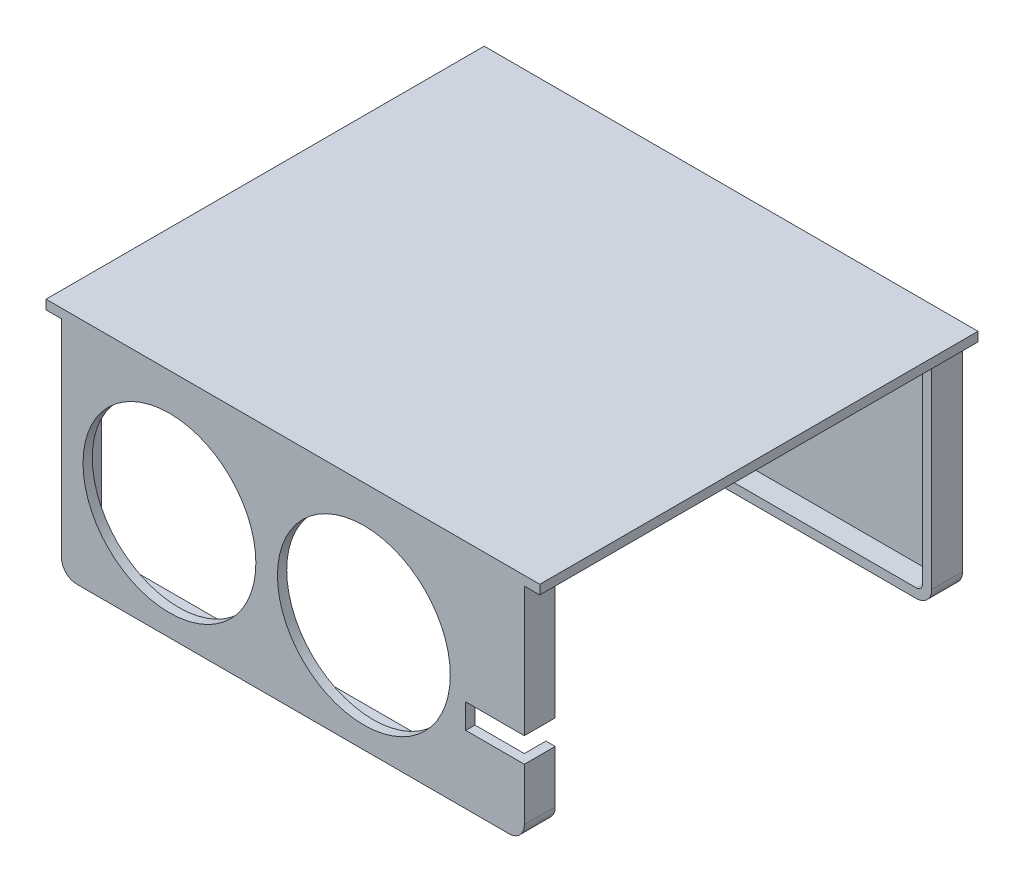
SolidWorks part; units mm, degrees
ref_plane "Front Plane" through (0, 0, 0) normal (0, 0, 1) x (1, 0, 0)
ref_plane "Top Plane" through (0, 0, 0) normal (0, 1, 0) x (1, 0, 0)
ref_plane "Right Plane" through (0, 0, 0) normal (1, 0, 0) x (0, 0, -1)
sketch "MAX XY PROFILE" plane through (0, 0, 0) normal (0, 1, 0) x (1, 0, 0)
  line L1 (-45, 32) -> (115, 32)
  line L2 (-45, 32) -> (-45, -110)
  line L3 (-45, -110) -> (115, -110)
  line L4 (115, 32) -> (115, -110)
  dimension "D1" = 160
  dimension "D2" = 142
  dimension "D3" = 45
  dimension "D4" = 32
sketch "Sketch1" plane through (0, 0, 0) normal (0, 1, 0) x (1, 0, 0)
  line L0 (-45, 32) -> (115, 32) construction
  line L1 (115, 32) -> (115, -110) construction
  line L2 (-45, -110) -> (115, -110) construction
  line L3 (-45, 32) -> (-45, -110) construction
  line L4 (-45, 32) -> (115, 32)
  line L5 (115, 32) -> (115, -110)
  line L6 (-45, -110) -> (115, -110)
  line L7 (-45, 32) -> (-45, -110)
extrude "ROOF" add sketch "Sketch1" along normal blind 3
sketch "Sketch2" plane through (0, 0, 0) normal (0, 1, 0) x (1, 0, 0)
  line L0 (-45, 32) -> (115, 32) construction
  line L1 (-40, 32) -> (110, 32)
  line L2 (-40, 32) -> (-40, 29)
  line L3 (-40, 29) -> (110, 29)
  line L4 (110, 32) -> (110, 29)
  line L5 (-45, -110) -> (115, -110) construction
  line L6 (-40, -110) -> (110, -110)
  line L7 (-40, -110) -> (-40, -107)
  line L8 (-40, -107) -> (110, -107)
  line L9 (110, -110) -> (110, -107)
  line L10 (115, 32) -> (115, -110) construction
  dimension "D1" = 5
  dimension "D2" = 5
  dimension "D3" = 3
extrude "FRONT AND REAR WALLS" add sketch "Sketch2" against normal blind 72
fillet "Fillet1" radius 5 4 edges at (110, -72, -30.5) (-40, -72, -30.5) (110, -72, 108.5) (-40, -72, 108.5)
sketch "Sketch3" plane through (0, 0, 110) normal (0, 0, 1) x (1, 0, 0)
  line L0 (110, -67) -> (110, 0) construction
  line L1 (-35, -72) -> (105, -72) construction
  line L2 (-40, -67) -> (-40, 0) construction
  line L3 (110, -67) -> (110, 0)
  line L4 (-35, -72) -> (105, -72)
  line L5 (-40, -67) -> (-40, 0)
  line L6 (-37, -67) -> (-37, 0)
  line L7 (-35, -69) -> (105, -69)
  line L8 (107, -67) -> (107, 0)
  line L9 (107, 0) -> (110, 0)
  line L10 (-40, 0) -> (-37, 0)
  arc A0 (105, -72) -> (110, -67) centre (105, -67) ccw construction
  arc A1 (-40, -67) -> (-35, -72) centre (-35, -67) ccw construction
  arc A2 (105, -72) -> (110, -67) centre (105, -67) ccw
  arc A3 (-40, -67) -> (-35, -72) centre (-35, -67) ccw
  arc A4 (-37, -67) -> (-35, -69) centre (-35, -67) ccw
  arc A5 (105, -69) -> (107, -67) centre (105, -67) ccw
  dimension "D1" = 3
extrude "FRONT COVER REINFORCEMENT" add sketch "Sketch3" against normal blind 10
sketch "Sketch4" plane through (0, 0, -32) normal (0, 0, -1) x (-1, 0, 0)
  line L8 (-110, 0) -> (-110, -67)
  line L9 (-107, 0) -> (-110, 0)
  line L10 (-107, -67) -> (-107, 0)
  line L11 (35, -69) -> (-105, -69)
  line L12 (37, 0) -> (37, -67)
  line L13 (40, 0) -> (37, 0)
  line L14 (40, -67) -> (40, 0)
  line L15 (-105, -72) -> (35, -72)
  line L16 (-110, 0) -> (-110, -67)
  line L17 (-107, 0) -> (-110, 0)
  line L18 (-107, -67) -> (-107, 0)
  line L19 (35, -69) -> (-105, -69)
  line L20 (37, 0) -> (37, -67)
  line L21 (40, 0) -> (37, 0)
  line L22 (40, -67) -> (40, 0)
  line L23 (-105, -72) -> (35, -72)
  arc A4 (-107, -67) -> (-105, -69) centre (-105, -67) ccw
  arc A5 (35, -69) -> (37, -67) centre (35, -67) ccw
  arc A6 (35, -72) -> (40, -67) centre (35, -67) ccw
  arc A7 (-110, -67) -> (-105, -72) centre (-105, -67) ccw
  arc A8 (-107, -67) -> (-105, -69) centre (-105, -67) ccw
  arc A9 (35, -69) -> (37, -67) centre (35, -67) ccw
  arc A10 (35, -72) -> (40, -67) centre (35, -67) ccw
  arc A11 (-110, -67) -> (-105, -72) centre (-105, -67) ccw
  dimension "D1" = 0
extrude "REAR COVER REINFORCEMENT" add sketch "Sketch4" against normal blind 10
sketch "Sketch5" plane through (0, 0, 110) normal (0, 0, 1) x (1, 0, 0)
  line L0 (110, -50) -> (91, -50)
  line L1 (91, -50) -> (91, -42)
  line L2 (91, -42) -> (110, -42)
  line L3 (110, -42) -> (110, -50)
  dimension "D1" = 110
  dimension "D2" = 50
  dimension "D3" = 19
  dimension "D4" = 8
extrude "DISPLAY CABLE PASSTHRU CUT" cut sketch "Sketch5" against normal blind 10
sketch "Sketch6" plane through (0, 0, 110) normal (0, 0, 1) x (1, 0, 0)
  line L0 (-40, -67) -> (-40, 0) construction
  line L1 (-35, -72) -> (105, -72) construction
  circle A0 centre (-5, -37) radius 28
  circle A1 centre (58, -37) radius 28
  point P9 (0, 0)
  point P10 (0, 0)
  dimension "D1" = 56
  dimension "D2" = 35
  dimension "D3" = 63
  dimension "D4" = 35
extrude "FAN CUTOUTS" cut sketch "Sketch6" against normal blind 10
